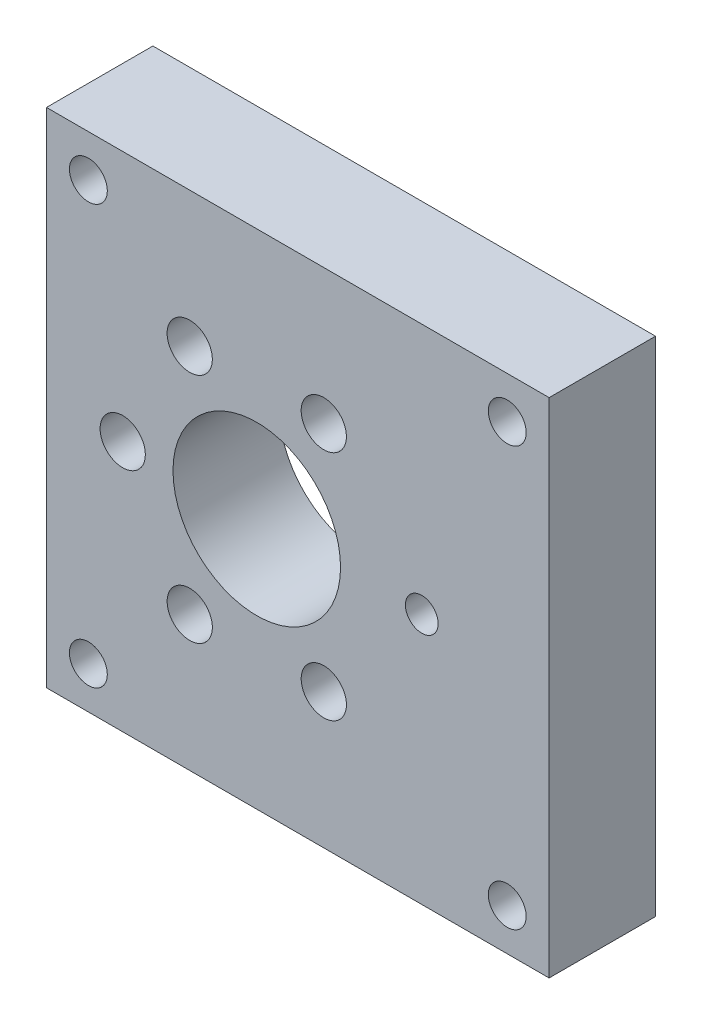
SolidWorks part; units mm, degrees
ref_plane "Front Plane" through (0, 0, 0) normal (0, 0, 1) x (1, 0, 0)
ref_plane "Top Plane" through (0, 0, 0) normal (0, 1, 0) x (1, 0, 0)
ref_plane "Right Plane" through (0, 0, 0) normal (1, 0, 0) x (0, 0, -1)
sketch "Sketch1" plane through (0, 0, 0) normal (0, 0, 1) x (1, 0, 0)
  line L1 (0, 0) -> (30, 0)
  line L2 (0, 0) -> (0, 30)
  line L3 (0, 30) -> (30, 30)
  line L4 (30, 0) -> (30, 30)
  dimension "D1" = 30
  dimension "D2" = 30
extrude "Boss-Extrude1" add sketch "Sketch1" along normal blind 6.35
hole_wizard "#2 Clearance Hole1" positions "Sketch3" profile "Sketch2" hole size "#2" standard "ANSI Inch" end condition through all
sketch "Sketch3" plane through (0, 0, 6.35) normal (0, 0, 1) x (1, 0, 0)
  line L0 (0, 27.5) -> (30, 27.5) construction
  line L1 (0, 30) -> (0, 0) construction
  line L2 (30, 0) -> (30, 30) construction
  line L4 (0, 15) -> (30, 15) construction
  line L6 (2.5, 30) -> (2.5, 0) construction
  line L7 (30, 30) -> (0, 30) construction
  line L8 (0, 0) -> (30, 0) construction
  line L11 (15, 30) -> (15, 0) construction
  point P21 (2.5, 27.5)
  point P32 (27.5, 27.5)
  point P34 (2.5, 2.5)
  point P35 (27.5, 2.5)
  dimension "D1" = 2.5
  dimension "D2" = 2.5
sketch "Sketch2" plane through (2.5, 27.5, 6.35) normal (1, 0, 0) x (0, -1, 0)
  line L0 (0, 0) -> (0, 6.35)
  line L1 (0, 6.35) -> (1.1303, 6.35)
  line L2 (1.1303, 6.35) -> (1.1303, 0)
  line L5 (1.1303, 0) -> (0, 0)
  line L11 (0, -6.35) -> (0, 107.95) construction
  dimension "Thru Hole Dia." = 2.2606
  dimension "Thru Hole Depth" = 6.35
sketch "Sketch4" plane through (0, 0, 6.35) normal (0, 0, 1) x (1, 0, 0)
  line L0 (0, 30) -> (0, 0) construction
  line L1 (0, 0) -> (30, 0) construction
  circle A0 centre (12.5501, 15.0012) radius 5
  dimension "D3" = 10
  dimension "D1" = 12.5501
  dimension "D2" = 15.0012
extrude "Cut-Extrude1" cut sketch "Sketch4" against normal through all
hole_wizard "M2.5 Clearance Hole1" positions "Sketch8" profile "Sketch7" hole size "M2.5" standard "ANSI Metric" end condition through all
sketch "Sketch8" plane through (0, 0, 6.35) normal (0, 0, 1) x (1, 0, 0)
  line L0 (0, 15) -> (12.5501, 15.0012) construction
  line L1 (0, 30) -> (0, 0) construction
  line L2 (12.5501, 15.0012) -> (16.5513, 8.0726) construction
  line L3 (12.5501, 15.0012) -> (16.5513, 8.0726) construction
  line L4 (12.5501, 15.0012) -> (8.5503, 8.0718) construction
  point P6 (16.5513, 8.0726)
  point P18 (8.5503, 8.0718)
  point P19 (4.5491, 15.0004)
  point P20 (8.549, 21.9299)
  point P21 (16.55, 21.9307)
  dimension "D1" = 60
  dimension "D3" = 60
  dimension "D4" = 8.001
  dimension "D2" = 5
sketch "Sketch7" plane through (16.5513, 8.0726, 6.35) normal (1, 0, 0) x (0, -1, 0)
  line L0 (0, 0) -> (0, 6.35)
  line L1 (0, 6.35) -> (1.35, 6.35)
  line L2 (1.35, 6.35) -> (1.35, 0)
  line L5 (1.35, 0) -> (0, 0)
  line L11 (0, -6.35) -> (0, 107.95) construction
  dimension "Thru Hole Dia." = 2.7
  dimension "Thru Hole Depth" = 6.35
sketch "Sketch9" plane through (0, 0, 6.35) normal (0, 0, 1) x (1, 0, 0)
  line L0 (0, 15) -> (30, 15) construction
  line L1 (0, 30) -> (0, 0) construction
  line L2 (30, 0) -> (30, 30) construction
  circle A0 centre (22.4003, 15) radius 0.9779
  dimension "D1" = 1.9558
  dimension "D2" = 7.5997
extrude "Cut-Extrude2" cut sketch "Sketch9" against normal through all
